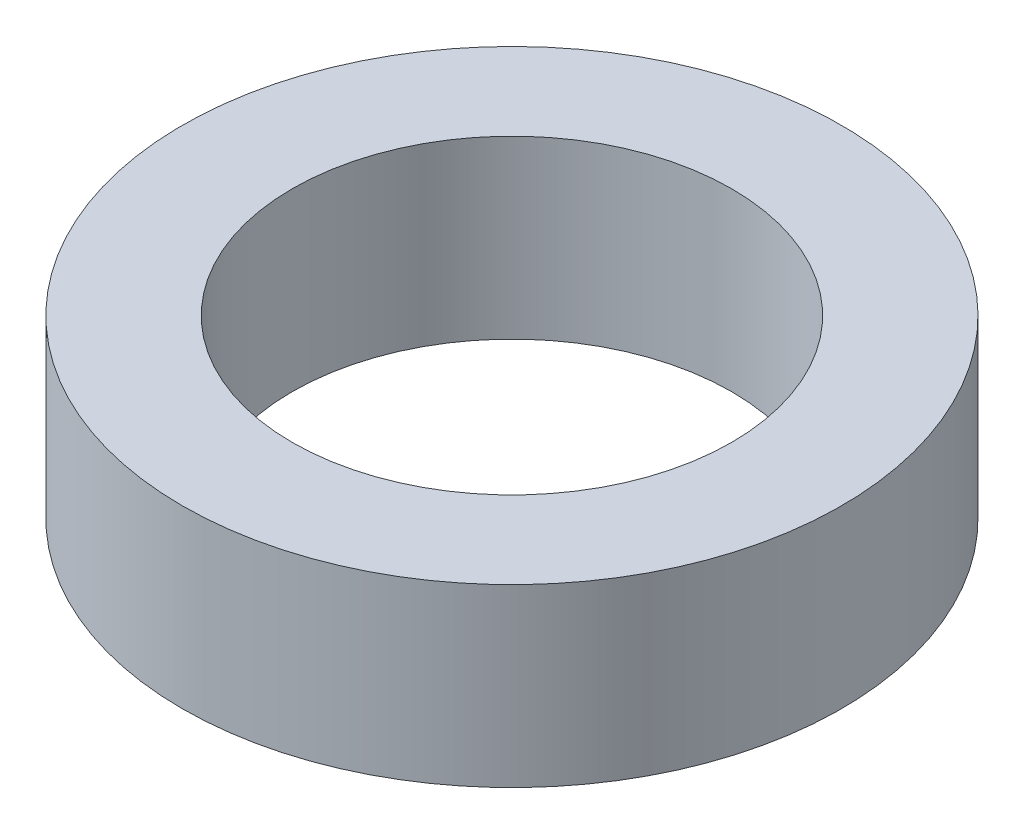
SolidWorks part; units mm, degrees
ref_plane "Front Plane" through (0, 0, 0) normal (0, 0, 1) x (1, 0, 0)
ref_plane "Top Plane" through (0, 0, 0) normal (0, 1, 0) x (1, 0, 0)
ref_plane "Right Plane" through (0, 0, 0) normal (1, 0, 0) x (0, 0, -1)
sketch "Sketch1" plane through (0, 0, 0) normal (0, 1, 0) x (1, 0, 0)
  circle A0 centre (0, 0) radius 5
  circle A1 centre (0, 0) radius 7.5
  dimension "D1" = 15
  dimension "D2" = 10
extrude "Boss-Extrude1" add sketch "Sketch1" along normal blind 4
